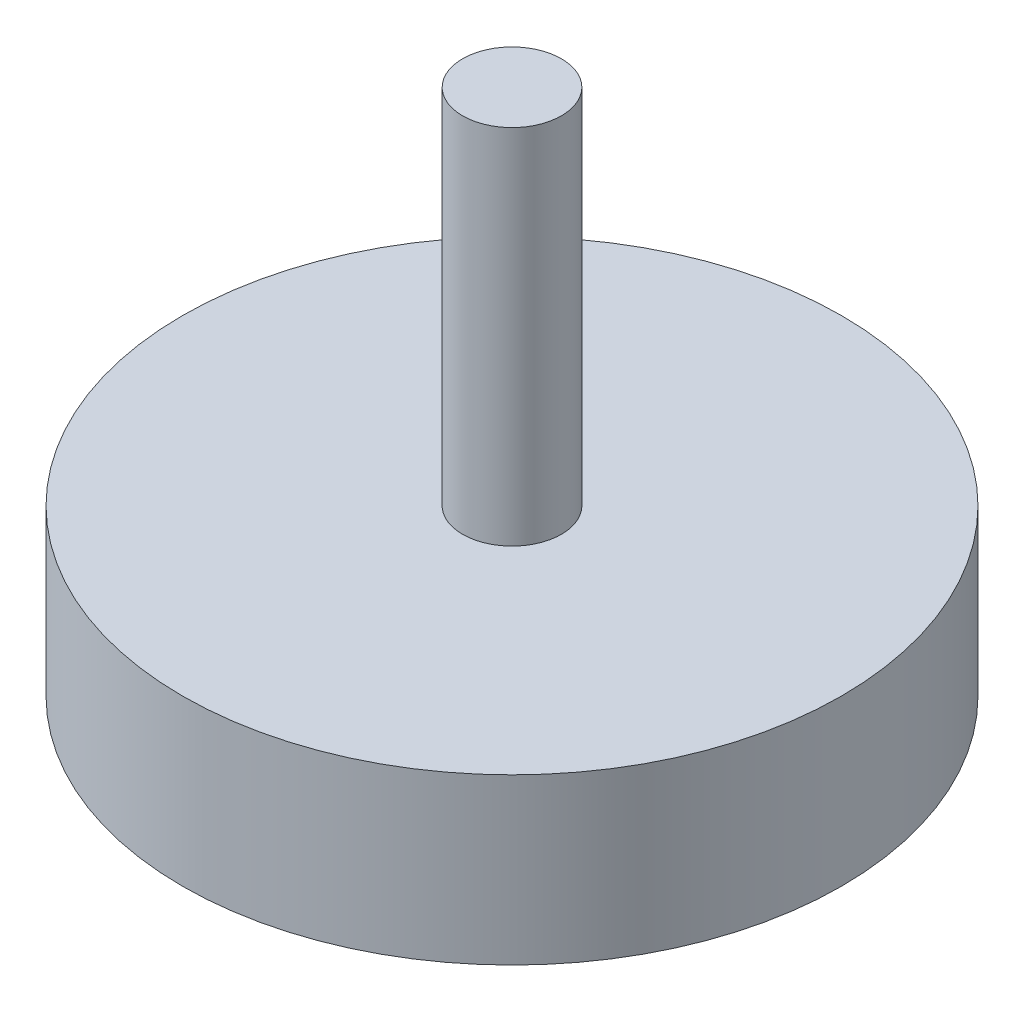
SolidWorks part; units mm, degrees
ref_plane "Front Plane" through (0, 0, 0) normal (0, 0, 1) x (1, 0, 0)
ref_plane "Top Plane" through (0, 0, 0) normal (0, 1, 0) x (1, 0, 0)
ref_plane "Right Plane" through (0, 0, 0) normal (1, 0, 0) x (0, 0, -1)
sketch "Sketch1" plane through (0, 0, 0) normal (0, 1, 0) x (1, 0, 0)
  circle A0 centre (0, 0) radius 50
  dimension "D1" = 100
extrude "Boss-Extrude1" add sketch "Sketch1" along normal blind 25
sketch "Sketch2" plane through (0, 25, 0) normal (0, 1, 0) x (1, 0, 0)
  circle A0 centre (0, 0) radius 7.5
  dimension "D1" = 15
extrude "Boss-Extrude2" add sketch "Sketch2" along normal blind 55
